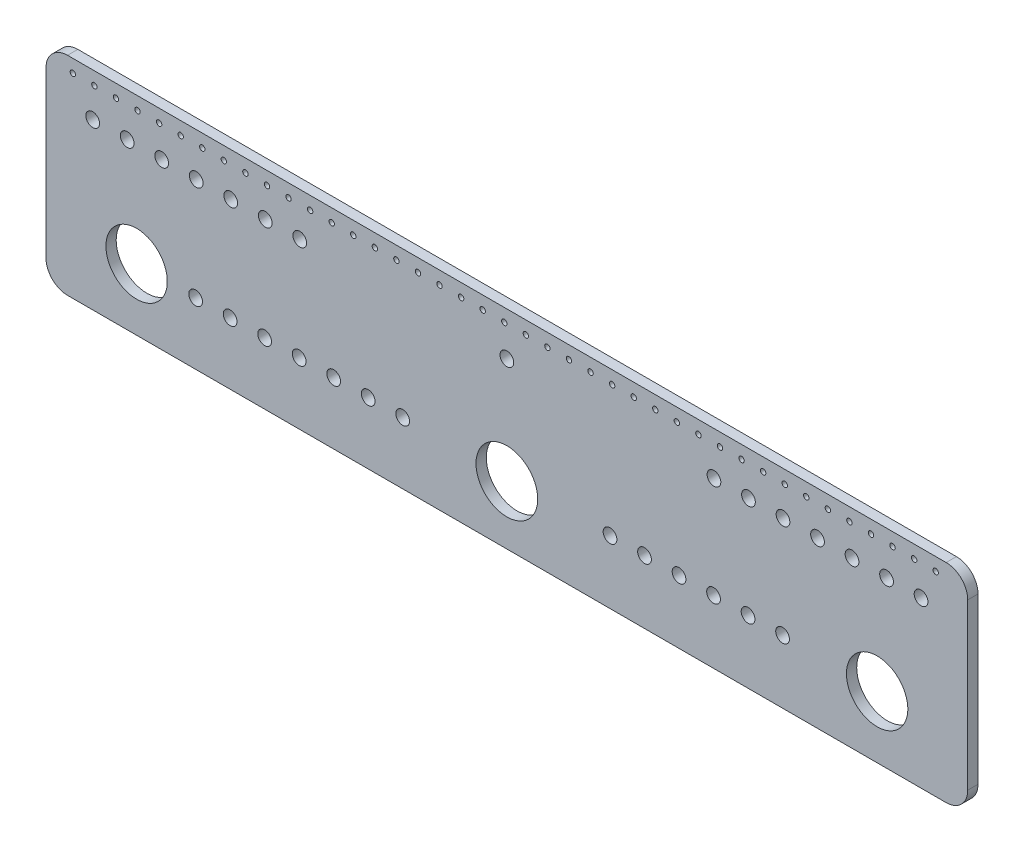
SolidWorks part; units mm, degrees
ref_plane "Front" through (0, 0, 0) normal (0, 0, 1) x (1, 0, 0)
ref_plane "Top" through (0, 0, 0) normal (0, 1, 0) x (1, 0, 0)
ref_plane "Right" through (0, 0, 0) normal (1, 0, 0) x (0, 0, -1)
sketch "Sketch1" plane through (0, 0, 0) normal (0, 0, 1) x (1, 0, 0)
  line L0 (-426.3498, 80.4904) -> (-19.0698, 80.4904)
  line L2 (-436.3498, 70.4904) -> (-436.3498, -5.9096)
  line L4 (-9.0698, 70.4904) -> (-9.0698, -5.9096)
  line L5 (-19.0698, -15.9096) -> (-426.3498, -15.9096)
  circle A0 centre (-394.3498, 12.7904) radius 14.225
  circle A1 centre (-51.0698, 12.7904) radius 14.225
  circle A11 centre (-222.7098, 11.2904) radius 14.3
  circle A54 centre (-174.8998, 13.3845) radius 3.18
  circle A151 centre (-366.9908, 12.7904) radius 3.18
  circle A159 centre (-94.8998, 13.3845) radius 3.18
  circle A286 centre (-350.9908, 12.7904) radius 3.18
  circle A288 centre (-334.9908, 12.7904) radius 3.18
  circle A290 centre (-318.9908, 12.7904) radius 3.18
  circle A292 centre (-302.9908, 12.7904) radius 3.18
  circle A294 centre (-286.9908, 12.7904) radius 3.18
  circle A296 centre (-158.8998, 13.3845) radius 3.18
  circle A297 centre (-142.8998, 13.3845) radius 3.18
  circle A298 centre (-126.8998, 13.3845) radius 3.18
  circle A299 centre (-110.8998, 13.3845) radius 3.18
  circle A314 centre (-270.9908, 12.7904) radius 3.18
  circle A402 centre (-213.9098, 74.4904) radius 1.25
  circle A441 centre (-30.7098, 60.4904) radius 3.18
  circle A447 centre (-414.7098, 60.4904) radius 3.18
  circle A448 centre (-203.9098, 74.4904) radius 1.25
  circle A449 centre (-193.9098, 74.4904) radius 1.25
  circle A450 centre (-183.9098, 74.4904) radius 1.25
  circle A451 centre (-173.9098, 74.4904) radius 1.25
  circle A452 centre (-163.9098, 74.4904) radius 1.25
  circle A453 centre (-153.9098, 74.4904) radius 1.25
  circle A454 centre (-143.9098, 74.4904) radius 1.25
  circle A455 centre (-133.9098, 74.4904) radius 1.25
  circle A456 centre (-123.9098, 74.4904) radius 1.25
  circle A457 centre (-113.9098, 74.4904) radius 1.25
  circle A458 centre (-103.9098, 74.4904) radius 1.25
  circle A459 centre (-93.9098, 74.4904) radius 1.25
  circle A460 centre (-83.9098, 74.4904) radius 1.25
  circle A461 centre (-73.9098, 74.4904) radius 1.25
  circle A462 centre (-63.9098, 74.4904) radius 1.25
  circle A463 centre (-53.9098, 74.4904) radius 1.25
  circle A464 centre (-43.9098, 74.4904) radius 1.25
  circle A465 centre (-33.9098, 74.4904) radius 1.25
  circle A466 centre (-23.9098, 74.4904) radius 1.25
  circle A469 centre (-223.9098, 74.4904) radius 1.25
  circle A470 centre (-233.9098, 74.4904) radius 1.25
  circle A471 centre (-243.9098, 74.4904) radius 1.25
  circle A472 centre (-253.9098, 74.4904) radius 1.25
  circle A473 centre (-263.9098, 74.4904) radius 1.25
  circle A474 centre (-273.9098, 74.4904) radius 1.25
  circle A475 centre (-283.9098, 74.4904) radius 1.25
  circle A476 centre (-293.9098, 74.4904) radius 1.25
  circle A477 centre (-303.9098, 74.4904) radius 1.25
  circle A478 centre (-313.9098, 74.4904) radius 1.25
  circle A479 centre (-323.9098, 74.4904) radius 1.25
  circle A480 centre (-333.9098, 74.4904) radius 1.25
  circle A481 centre (-343.9098, 74.4904) radius 1.25
  circle A482 centre (-353.9098, 74.4904) radius 1.25
  circle A483 centre (-363.9098, 74.4904) radius 1.25
  circle A484 centre (-373.9098, 74.4904) radius 1.25
  circle A485 centre (-383.9098, 74.4904) radius 1.25
  circle A486 centre (-393.9098, 74.4904) radius 1.25
  circle A487 centre (-403.9098, 74.4904) radius 1.25
  circle A488 centre (-413.9098, 74.4904) radius 1.25
  arc A538 (-426.3498, -15.9096) -> (-436.3498, -5.9096) centre (-426.3498, -5.9096) cw
  arc A539 (-426.3498, 80.4904) -> (-436.3498, 70.4904) centre (-426.3498, 70.4904) ccw
  arc A540 (-9.0698, 70.4904) -> (-19.0698, 80.4904) centre (-19.0698, 70.4904) ccw
  arc A541 (-9.0698, -5.9096) -> (-19.0698, -15.9096) centre (-19.0698, -5.9096) cw
  circle A552 centre (-423.9098, 74.4904) radius 1.25
  circle A554 centre (-222.7098, 60.4904) radius 3.18
  circle A627 centre (-398.7098, 60.4904) radius 3.18
  circle A628 centre (-382.7098, 60.4904) radius 3.18
  circle A629 centre (-366.7098, 60.4904) radius 3.18
  circle A630 centre (-350.7098, 60.4904) radius 3.18
  circle A631 centre (-334.7098, 60.4904) radius 3.18
  circle A632 centre (-318.7098, 60.4904) radius 3.18
  circle A645 centre (-46.7098, 60.4904) radius 3.18
  circle A646 centre (-62.7098, 60.4904) radius 3.18
  circle A647 centre (-78.7098, 60.4904) radius 3.18
  circle A648 centre (-94.7098, 60.4904) radius 3.18
  circle A649 centre (-110.7098, 60.4904) radius 3.18
  circle A650 centre (-126.7098, 60.4904) radius 3.18
  circle A664 centre (-3.9098, 74.4904) radius 1.25 [skipped]
  circle A667 centre (-423.9098, 74.4904) radius 1.25 [skipped]
  circle A668 centre (-13.9098, 74.4904) radius 1.25 [skipped]
  circle A681 centre (-142.7098, 44.4904) radius 3.18 [skipped]
  circle A682 centre (-126.7098, 44.4904) radius 3.18 [skipped]
  circle A683 centre (-302.7098, 44.4904) radius 3.18 [skipped]
  circle A684 centre (-318.7098, 44.4904) radius 3.18 [skipped]
  circle A685 centre (-302.7098, 60.4904) radius 3.18 [skipped]
  circle A686 centre (-142.7098, 60.4904) radius 3.18 [skipped]
  circle A687 centre (-46.7098, 44.4904) radius 3.18 [skipped]
  circle A688 centre (-62.7098, 44.4904) radius 3.18 [skipped]
  circle A689 centre (-30.7098, 44.4904) radius 3.18 [skipped]
  circle A690 centre (-78.7098, 44.4904) radius 3.18 [skipped]
  circle A691 centre (-94.7098, 44.4904) radius 3.18 [skipped]
  circle A692 centre (-110.7098, 44.4904) radius 3.18 [skipped]
  circle A693 centre (-334.7098, 44.4904) radius 3.18 [skipped]
  circle A694 centre (-350.7098, 44.4904) radius 3.18 [skipped]
  circle A695 centre (-366.7098, 44.4904) radius 3.18 [skipped]
  circle A696 centre (-414.7098, 44.4904) radius 3.18 [skipped]
  circle A697 centre (-398.7098, 44.4904) radius 3.18 [skipped]
  circle A698 centre (-382.7098, 44.4904) radius 3.18 [skipped]
  point P45 (-0.2698, -21.5096)
  point P52 (-0.2698, 90.4904)
  dimension "D2" = 42
  dimension "D4" = 42
  dimension "D6" = 222.44
  dimension "D12" = 171.64
  dimension "D13" = 22
  dimension "D14" = 10
  dimension "D15" = 10
  dimension "D16" = 2
  dimension "D17" = 10
  dimension "D23" = 8
  dimension "D27" = 2
  dimension "D28" = 20
  dimension "D29" = 14
  dimension "D24" = 2
  dimension "D25" = 171.64
  dimension "D26" = 10
  dimension "D1" = 112
  dimension "D7" = 6
  dimension "D9" = 5
  dimension "D11" = 22
  dimension "D19" = 8
  dimension "D22" = 2
extrude "Boss-Extrude5" add sketch "Sketch1" along normal blind 4.7625
move or copy body "Body-Move/Copy1" [suppressed]
